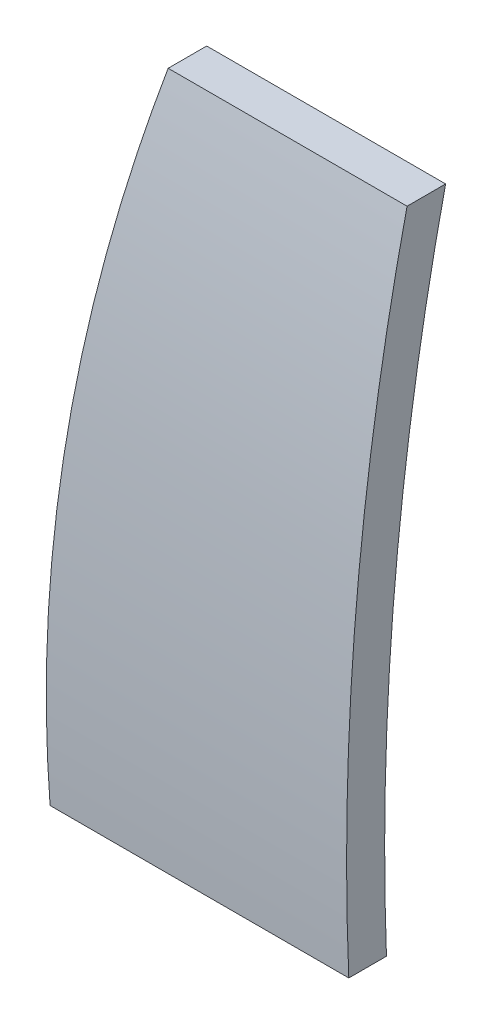
SolidWorks part; units mm, degrees
material "Glass"
ref_plane "Front Plane" through (0, 0, 0) normal (0, 0, 1) x (1, 0, 0)
ref_plane "Top Plane" through (0, 0, 0) normal (0, 1, 0) x (1, 0, 0)
ref_plane "Right Plane" through (0, 0, 0) normal (1, 0, 0) x (0, 0, -1)
sketch "Sketch1" plane through (0, 0, 0) normal (0, 0, 1) x (1, 0, 0)
  line L0 (121.1841, 1295.4) -> (605.3081, 1295.4)
  line L1 (0, 0) -> (605.3081, 0)
  line L2 (605.3081, 1295.4) -> (605.3081, 0)
  arc A1 (121.1841, 1295.4) -> (0, 0) centre (5038.2212, 182.0449) ccw
  dimension "D3" = 605.3081
  dimension "D4" = 5041.509
  dimension "D5" = 182.0449
  dimension "D1" = 484.124
  dimension "D2" = 1295.4
extrude "Boss-Extrude1" add sketch "Sketch1" along normal mid plane 508
sketch "Sketch2" plane through (0, 0, 0) normal (1, 0, 0) x (0, 0, -1)
  line L1 (196.1868, 1295.4) -> (254, 1295.4)
  line L3 (254, 1295.4) -> (254, 0)
  line L4 (254, 0) -> (76.2672, 0)
  line L5 (118.0703, 1295.4) -> (-254, 1295.4)
  line L7 (0, 0) -> (76.2672, 0)
  line L8 (196.1868, 1295.4) -> (118.0703, 1295.4)
  line L10 (-254, 1295.4) -> (-254, 0)
  line L11 (-254, 0) -> (0, 0)
  arc A0 (196.1868, 1295.4) -> (76.2672, 0) centre (5078.4821, 190.1785) ccw
  arc A1 (118.0703, 1295.4) -> (0, 0) centre (4873.7213, 208.8614) ccw
  spline S4 degree 3 poles (118.0703, 1295.4) (94.5648, 1190.445) (74.2845, 1084.7664) (40.4506, 871.8984) (26.8971, 764.7092) (6.8137, 548.7534) (0.2837, 439.9866) (-3.2892, 302.9971) (-3.7742, 275.5476) (-4.1536, 234.2952) (-4.2562, 213.6494) (-4.2275, 192.9741) (-4.1791, 179.184) (-4.1402, 172.2852) (-3.659, 110.214) (-2.2952, 55.0846) (0, 0) knots 0 0 0 0 0.25 0.25 0.5 0.5 0.75 0.75 0.8125 0.8125 0.84375 0.859375 0.859375 0.875 0.875 1 1 1 1
  spline S5 degree 3 poles (76.2672, 0) (75.1005, 27.5617) (73.7059, 68.9228) (72.7021, 117.2098) (72.4057, 137.9111) (72.2378, 151.7136) (72.1687, 158.6169) (71.6812, 220.7208) (72.2017, 275.7138) (76.5602, 440.0755) (83.1946, 548.8269) (103.5954, 764.7556) (117.362, 871.933) (151.7238, 1084.781) (172.319, 1190.4514) (196.1868, 1295.4) knots 0 0 0 0 0.0625 0.09375 0.109375 0.109375 0.125 0.125 0.25 0.25 0.5 0.5 0.75 0.75 1 1 1 1
extrude "Cut-Extrude1" cut sketch "Sketch2" along normal through all and the other way through all contours L1 A0 L4 L3 | A1 L5 L10 L11
ref_plane "Plane1" through (607.8481, 0, 0) normal (1, 0, 0) x (0, 0, -1)
ref_plane "Plane2" through (-3.2878, 0, 0) normal (-1, 0, 0) x (0, 0, 1)
